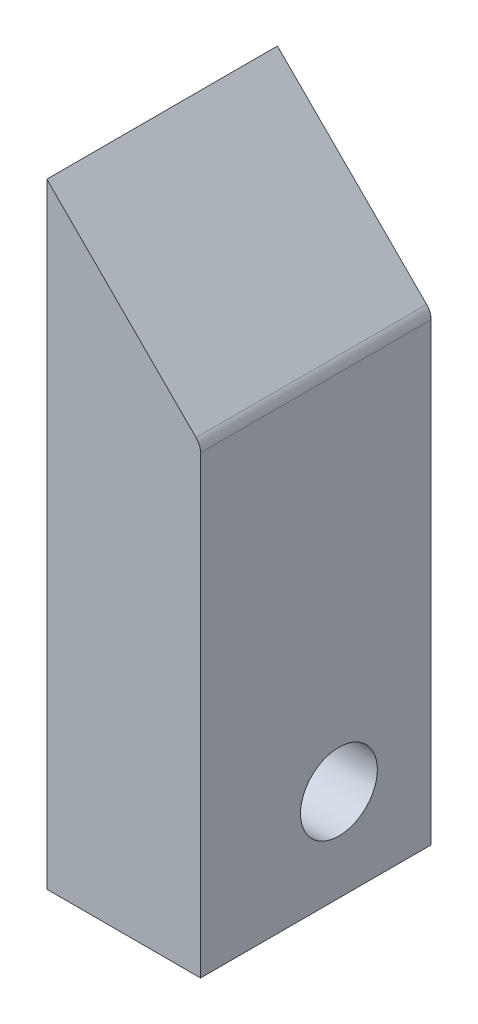
SolidWorks part; units mm, degrees
material "Acrílico (médio-alto impacto)"
ref_plane "Plano frontal" through (0, 0, 0) normal (0, 0, 1) x (1, 0, 0)
ref_plane "Plano superior" through (0, 0, 0) normal (0, 1, 0) x (1, 0, 0)
ref_plane "Plano direito" through (0, 0, 0) normal (1, 0, 0) x (0, 0, -1)
sketch "Esboço1" plane through (0, 0, 0) normal (0, 0, 1) x (1, 0, 0)
  line L0 (0, 0) -> (0, 40)
  line L1 (0, 40) -> (10, 30)
  line L2 (10, 30) -> (10, 0)
  line L3 (10, 0) -> (0, 0)
  dimension "D1" = 40
  dimension "D2" = 30
  dimension "D3" = 10
extrude "Ressalto-extrusão1" add sketch "Esboço1" along normal blind 15
sketch "Esboço2" plane through (10, 0, 0) normal (1, 0, 0) x (0, 0, -1)
  line L0 (0, 0) -> (0, 30) construction
  line L1 (-15, 0) -> (0, 0) construction
  circle A0 centre (-6, 6) radius 2.5
  dimension "D1" = 5
  dimension "D2" = 6
  dimension "D3" = 6
extrude "Corte-extrusão1" cut sketch "Esboço2" against normal through all
sketch "Esboço3" plane through (0, 0, 0) normal (0, 0, -1) x (-1, 0, 0)
  line L0 (0, 40) -> (0, 0) construction
  line L1 (0, 0) -> (-10, 0) construction
  line L2 (-2.5, 8.5) -> (0, 8.5)
  line L3 (-2.5, 3.5) -> (0, 3.5)
  line L4 (0, 3.5) -> (0, 8.5)
  circle A0 centre (-2.5, 6) radius 2.5
  line M8 (0, 0) -> (0, 40)
  dimension "D1" = 5
  dimension "D2" = 2.5
  dimension "D3" = 6
extrude "Corte-extrusão2" cut sketch "Esboço3" against normal blind 6 contours A0 | A0 L4 L2 | A0 L3 M8
fillet "Filete1" radius 1 1 edges at (10, 30, 7.5)
